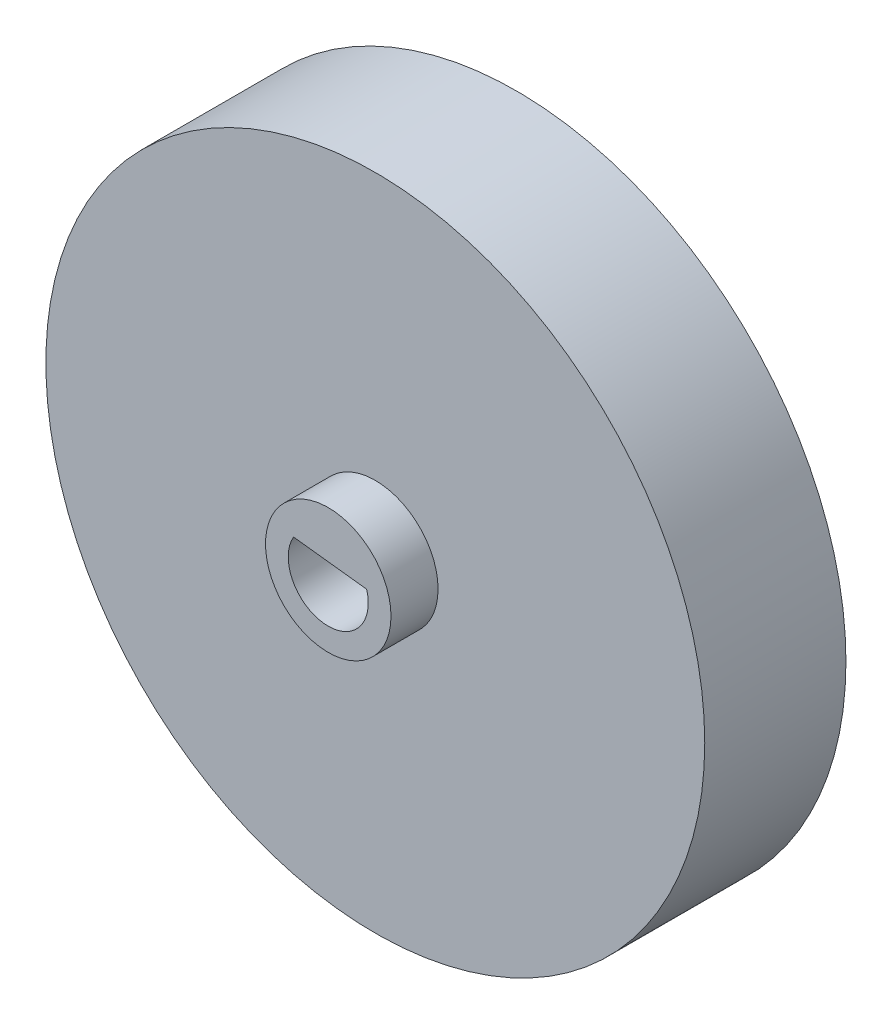
SolidWorks part; units mm, degrees
ref_plane "前视基准面" through (0, 0, 0) normal (0, 0, 1) x (1, 0, 0)
ref_plane "上视基准面" through (0, 0, 0) normal (0, 1, 0) x (1, 0, 0)
ref_plane "右视基准面" through (0, 0, 0) normal (1, 0, 0) x (0, 0, -1)
other "Configuration Table"
sketch "草图1" plane through (0, 0, 0) normal (0, 0, 1) x (1, 0, 0)
  line L0 (4.894, 1.4347) -> (-4.4239, 2.5376)
  circle A0 centre (0, 0) radius 8
  arc A1 (-4.4239, 2.5376) -> (4.894, 1.4347) centre (0, 0) ccw
extrude "凸台-拉伸1" add sketch "草图1" along normal blind 24
sketch "草图2" plane through (0, 0, 0) normal (0, 0, 1) x (1, 0, 0)
  circle A0 centre (0, 0) radius 42
  circle A1 centre (0, 0) radius 8
extrude "凸台-拉伸2" add sketch "草图2" along normal blind 18
sketch "草图3" plane through (0, 0, 0) normal (0, 0, 1) x (1, 0, 0)
  line L0 (37.5326, 2.0353) -> (41.987, 1.0447)
  line L1 (41.987, -1.0447) -> (37.5326, -2.0353)
  arc A0 (37.5326, -2.0353) -> (37.5326, 2.0353) centre (0, 0) ccw
  circle A1 centre (0, 0) radius 42 construction
  arc A2 (41.987, 1.0447) -> (41.987, -1.0447) centre (0, 0) cw
extrude "凸台-拉伸3" add sketch "草图3" along normal blind 18
